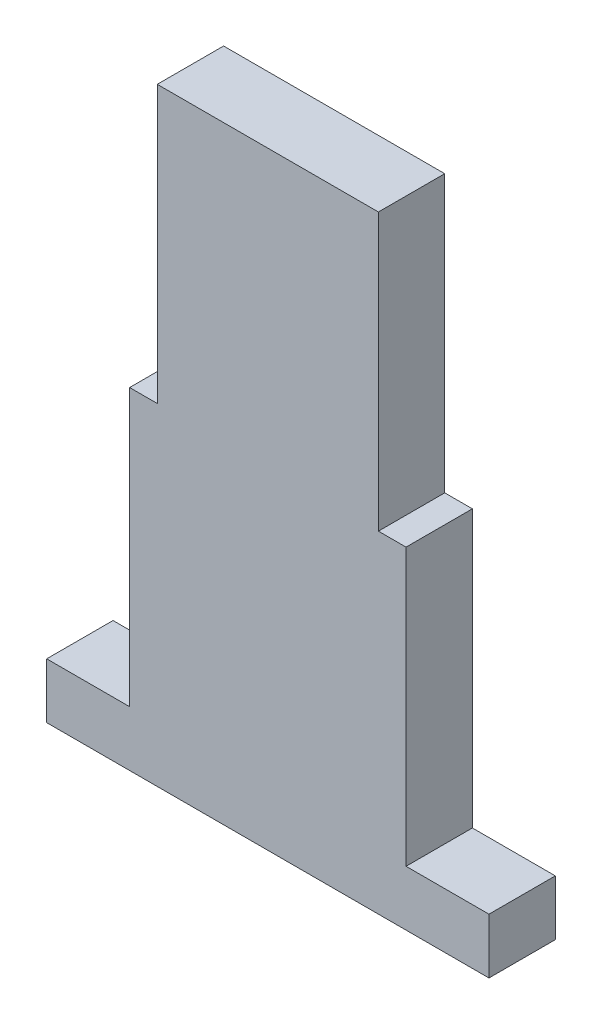
SolidWorks part; units mm, degrees
ref_plane "Front Plane" through (0, 0, 0) normal (0, 0, 1) x (1, 0, 0)
ref_plane "Top Plane" through (0, 0, 0) normal (0, 1, 0) x (1, 0, 0)
ref_plane "Right Plane" through (0, 0, 0) normal (1, 0, 0) x (0, 0, -1)
sketch "Sketch1" plane through (0, 0, 0) normal (0, 0, 1) x (1, 0, 0)
  line L0 (55, 0) -> (-55, 0) construction
  line L2 (-2.5, 0) -> (-2.5, 5)
  line L3 (-2.5, 5) -> (-2, 5)
  line L4 (2.5, 0) -> (2.5, 5)
  line L5 (-2, 10) -> (2, 5) construction
  line L7 (2, 5) -> (2, 10)
  line L8 (2, 10) -> (-2, 10)
  line L9 (-2, 5) -> (-2, 10)
  line L10 (2.5, 5) -> (-2.5, 0) construction
  line L11 (0, -55) -> (0, 55) construction
  line L12 (2, 5) -> (2.5, 5)
  line L13 (-4, 0) -> (4, -1) construction
  line L14 (-4, 0) -> (-2.5, 0)
  line L15 (-4, 0) -> (-4, -1)
  line L16 (-4, -1) -> (4, -1)
  line L17 (4, 0) -> (4, -1)
  line L18 (2.5, 0) -> (4, 0)
  point P10 (0, 2.5)
  point P13 (0, 7.5)
  point P18 (0, -0.5)
  dimension "D1" = 4
  dimension "D2" = 5
  dimension "D3" = 5
  dimension "D4" = 5
  dimension "D5" = 1
  dimension "D6" = 8
extrude "Boss-Extrude1" add sketch "Sketch1" along normal mid plane 1.2
